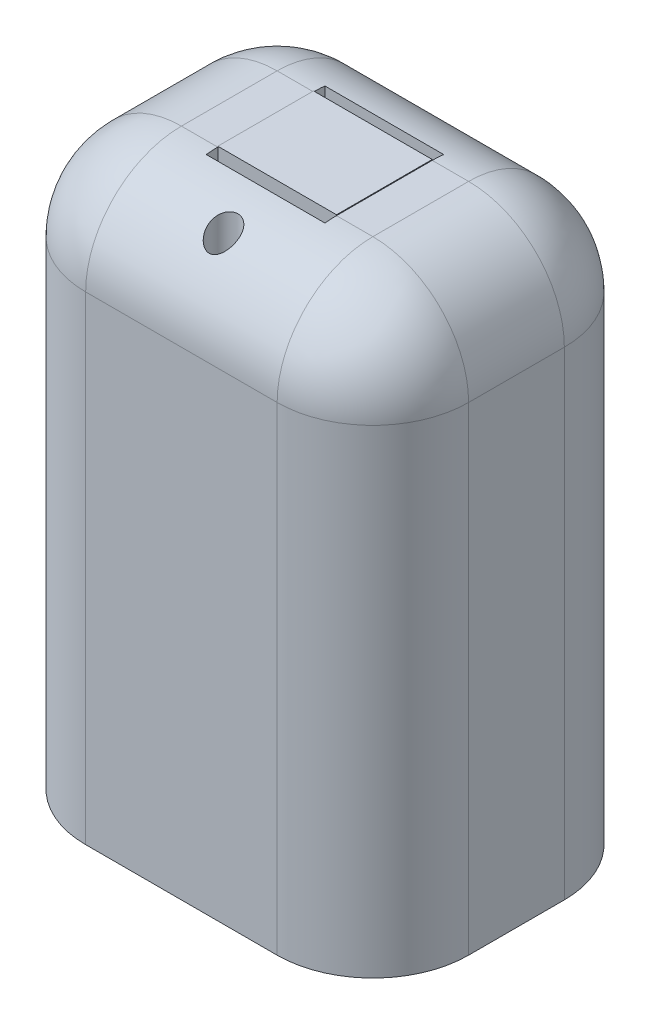
SolidWorks part; units mm, degrees
ref_plane "Front Plane" through (0, 0, 0) normal (0, 0, 1) x (1, 0, 0)
ref_plane "Top Plane" through (0, 0, 0) normal (0, 1, 0) x (1, 0, 0)
ref_plane "Right Plane" through (0, 0, 0) normal (1, 0, 0) x (0, 0, -1)
sketch "Sketch1" plane through (0, 0, 0) normal (0, 0, 1) x (1, 0, 0)
  line L1 (-46.2655, 135.4082) -> (-26.2655, 135.4082)
  line L2 (-46.2655, 135.4082) -> (-46.2655, 105.4082)
  line L3 (-46.2655, 105.4082) -> (-26.2655, 105.4082)
  line L4 (-26.2655, 135.4082) -> (-26.2655, 105.4082)
  line L5 (-46.2655, 135.4082) -> (-26.2655, 105.4082) construction
  line L6 (-46.2655, 105.4082) -> (-26.2655, 135.4082) construction
  point P0 (-36.2655, 120.4082)
  dimension "D1" = 20
  dimension "D2" = 30
extrude "Boss-Extrude1" add sketch "Sketch1" along normal blind 15
sketch "Sketch2" plane through (0, 105.4082, 0) normal (0, -1, 0) x (-1, 0, 0)
  line L0 (36.2655, -15) -> (36.2655, -7.5) construction
  line L1 (39.3655, -4.4) -> (33.1655, -4.4)
  line L2 (39.3655, -4.4) -> (39.3655, -10.6)
  line L3 (39.3655, -10.6) -> (33.1655, -10.6)
  line L4 (33.1655, -4.4) -> (33.1655, -10.6)
  line L5 (39.3655, -4.4) -> (33.1655, -10.6) construction
  line L6 (39.3655, -10.6) -> (33.1655, -4.4) construction
  line L7 (46.2655, -15) -> (26.2655, -15) construction
  line L8 (36.2655, -7.5) -> (26.2655, -7.5) construction
  line L9 (26.2655, -15) -> (26.2655, 0) construction
  point P0 (36.2655, -7.5)
  dimension "D1" = 6.2
  dimension "D2" = 6.2
extrude "Cut-Extrude1" cut sketch "Sketch2" against normal blind 3.25
fillet "Fillet1" radius 5 8 edges at (-26.2655, 135.4082, 7.5) (-36.2655, 135.4082, 15) (-46.2655, 135.4082, 7.5) (-36.2655, 135.4082, 0) (-46.2655, 120.4082, 0) (-46.2655, 120.4082, 15) (-26.2655, 120.4082, 0) (-26.2655, 120.4082, 15)
sketch "Sketch4" plane through (0, 108.6582, 0) normal (0, -1, 0) x (1, 0, 0)
  line L0 (-39.3655, 10.6) -> (-33.1655, 10.6)
  line L1 (-33.1655, 10.6) -> (-33.1655, 4.4)
  line L2 (-33.1655, 4.4) -> (-39.3655, 4.4)
  line L3 (-39.3655, 4.4) -> (-39.3655, 10.6)
extrude "Cut-Extrude2" cut sketch "Sketch4" against normal blind 68
sketch "Sketch6" plane through (-39.3655, 0, 0) normal (1, 0, 0) x (0, 0, -1)
  line L0 (-10, 135.4082) -> (-10, 130.4082) construction
  line L1 (-10, 135.4497) -> (-5, 135.4497)
  line L2 (-10, 135.4497) -> (-10, 134.4497)
  line L3 (-10, 134.4497) -> (-5, 134.4497)
  line L4 (-5, 135.4497) -> (-5, 134.4497)
  line L5 (-5, 130.4082) -> (-5, 135.4082) construction
  dimension "D1" = 1
  dimension "D2" = 5
extrude "Boss-Extrude3" add sketch "Sketch6" along normal blind 6.2
sketch "Sketch7" plane through (0, 105.4082, 0) normal (0, -1, 0) x (1, 0, 0)
  line L0 (-36.2655, 10.6) -> (-36.2655, 15) construction
  line L1 (-33.1655, 10.6) -> (-39.3655, 10.6) construction
  line L2 (-41.2655, 15) -> (-31.2655, 15) construction
  circle A0 centre (-36.2655, 12.8) radius 0.75
extrude "Cut-Extrude3" cut sketch "Sketch7" against normal blind 37
